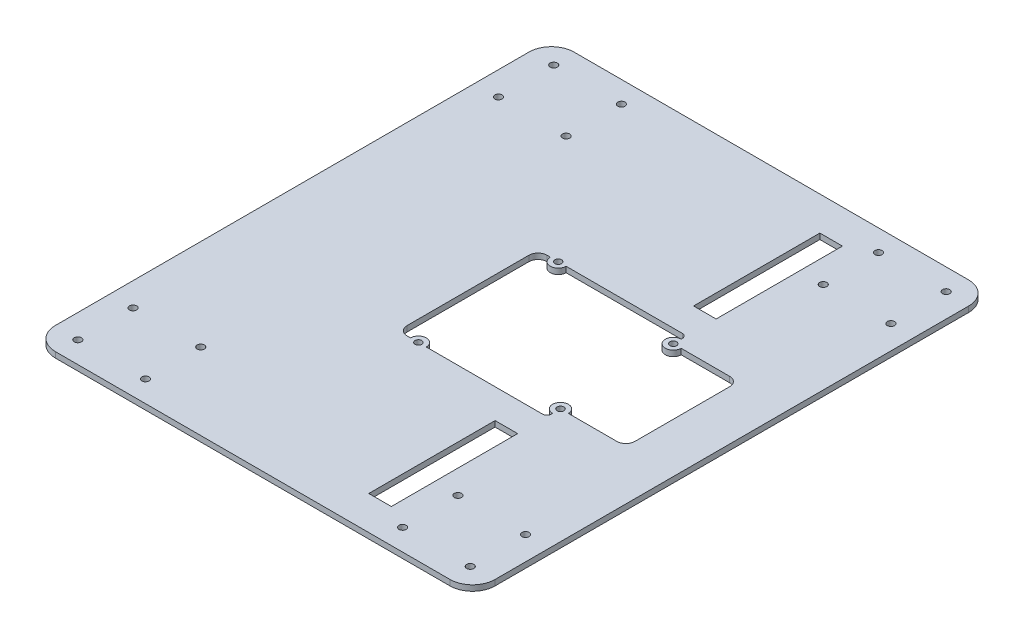
SolidWorks part; units mm, degrees
ref_plane "前视基准面" through (0, 0, 0) normal (0, 0, 1) x (1, 0, 0)
ref_plane "上视基准面" through (0, 0, 0) normal (0, 1, 0) x (1, 0, 0)
ref_plane "右视基准面" through (0, 0, 0) normal (1, 0, 0) x (0, 0, -1)
other "Configuration Table"
sketch "草图1" plane through (0, 0, 0) normal (0, 1, 0) x (1, 0, 0)
  line L0 (134, 15) -> (144, 15)
  line L1 (134, 215) -> (144, 215)
  line L5 (25.5, 220.5) -> (25.5, 196) construction
  line L9 (10.5, 220.5) -> (40.5, 220.5) construction
  line L10 (10.5, 220.5) -> (10.5, 196) construction
  line L43 (10.5, 196) -> (40.5, 196) construction
  line L44 (40.5, 220.5) -> (40.5, 196) construction
  line L45 (10.5, 208.25) -> (40.5, 208.25) construction
  line L46 (97.5, 230) -> (97.5, 0) construction
  line L47 (0, 0) -> (195, 0)
  line L48 (0, 0) -> (0, 230)
  line L49 (0, 230) -> (195, 230)
  line L50 (195, 0) -> (195, 230)
  line L51 (0, 230) -> (51, 230)
  line L52 (0, 230) -> (0, 186)
  line L53 (0, 186) -> (51, 186)
  line L54 (51, 230) -> (51, 186)
  line L55 (195, 230) -> (144, 230)
  line L56 (195, 230) -> (195, 186)
  line L57 (195, 186) -> (144, 186)
  line L58 (144, 230) -> (144, 186)
  line L59 (0, 0) -> (51, 0)
  line L60 (0, 0) -> (0, 44)
  line L61 (0, 44) -> (51, 44)
  line L62 (51, 0) -> (51, 44)
  line L63 (195, 0) -> (144, 0)
  line L64 (195, 0) -> (195, 44)
  line L65 (195, 44) -> (144, 44)
  line L66 (144, 0) -> (144, 44)
  line L67 (144, 230) -> (134, 230)
  line L68 (144, 230) -> (144, 159)
  line L69 (144, 159) -> (134, 159)
  line L70 (134, 230) -> (134, 159)
  line L71 (144, 0) -> (134, 0)
  line L72 (144, 0) -> (144, 71)
  line L73 (144, 71) -> (134, 71)
  line L74 (134, 0) -> (134, 71)
  line L75 (195, 115) -> (0, 115) construction
  circle A0 centre (10.5, 220.5) radius 1.6
  circle A1 centre (40.5, 220.5) radius 1.6
  circle A2 centre (40.5, 196) radius 1.6
  circle A3 centre (10.5, 196) radius 1.6
  circle A4 centre (184.5, 220.5) radius 1.6
  circle A5 centre (154.5, 220.5) radius 1.6
  circle A6 centre (154.5, 196) radius 1.6
  circle A7 centre (184.5, 196) radius 1.6
  circle A8 centre (154.5, 34) radius 1.6
  circle A9 centre (184.5, 34) radius 1.6
  circle A10 centre (184.5, 9.5) radius 1.6
  circle A11 centre (154.5, 9.5) radius 1.6
  circle A12 centre (40.5, 9.5) radius 1.6
  circle A13 centre (40.5, 34) radius 1.6
  circle A14 centre (10.5, 34) radius 1.6
  circle A15 centre (10.5, 9.5) radius 1.6
  point P4 (139, 15)
  point P5 (139, 71)
  dimension "D24" = 3.2
  dimension "D3" = 56
  dimension "D4" = 15
  dimension "D5" = 56
  dimension "D6" = 15
  dimension "D8" = 30
  dimension "D9" = 24.5
  dimension "D10" = 195
  dimension "D11" = 230
  dimension "D12" = 51
  dimension "D13" = 44
  dimension "D14" = 51
  dimension "D15" = 44
  dimension "D16" = 51
  dimension "D17" = 44
  dimension "D18" = 51
  dimension "D19" = 44
  dimension "D20" = 10
  dimension "D21" = 10
  dimension "D25" = 9.5
  dimension "D26" = 25.5
extrude "凸台-拉伸1" add sketch "草图1" along normal blind 2.5 contours L47 L74 L73 L72 L65 L50 L57 L68 L69 L70 L49 L54 L53 L48 L61 L62 | L54 L49 L48 L53 A3 A2 A1 A0 | L49 L58 L57 L50 A6 A4 A5 A7 | L47 L62 L61 L48 A14 A12 A13 A15 | L66 L47 L50 L65 A11 A10 A9 A8 | L74 L47 L66 L0 | L49 L70 L1 L58
sketch "草图2" plane through (0, 2.5, 0) normal (0, 1, 0) x (1, 0, 0)
  line L0 (0, 115) -> (195, 115) construction
  line L1 (87, 84) -> (87, 146) construction
  line L2 (144, 90) -> (144, 140) construction
  line L4 (78, 84) -> (144, 84)
  line L5 (78, 84) -> (78, 146)
  line L6 (78, 146) -> (144, 146)
  line L7 (144, 84) -> (144, 146)
  line L8 (144, 90) -> (173, 90)
  line L9 (144, 90) -> (144, 140)
  line L10 (144, 140) -> (173, 140)
  line L11 (173, 90) -> (173, 140)
  line L12 (0, 0) -> (195, 0)
  line L17 (195, 0) -> (195, 230)
  line L18 (195, 230) -> (0, 230)
  line L23 (0, 230) -> (0, 0)
  line L24 (0, 0) -> (195, 0)
  line L29 (195, 0) -> (195, 230)
  line L30 (195, 230) -> (0, 230)
  line L35 (0, 230) -> (0, 0)
  circle A0 centre (144, 90) radius 1.5
  circle A2 centre (87, 146) radius 1.5
  circle A3 centre (87, 84) radius 1.5
  circle A4 centre (144, 140) radius 1.5
  circle A5 centre (144, 90) radius 3.5
  circle A6 centre (144, 140) radius 3.5
  circle A7 centre (87, 84) radius 3.5
  circle A8 centre (87, 146) radius 3.5
  dimension "D4" = 3
  dimension "D5" = 3
  dimension "D10" = 7
  dimension "D11" = 7
  dimension "D12" = 7
  dimension "D13" = 7
  dimension "D2" = 50
  dimension "D3" = 62
  dimension "D6" = 57
  dimension "D8" = 95
  dimension "D9" = 66
  dimension "D1" = 0
extrude "切除-拉伸1" cut sketch "草图2" against normal up to surface (2.5 mm away) contours A3 L4 L7 L6 A2 L5 | A4 L10 L7 L8 A0 L11 | L8 A0 | L8 A0 | L10 A4 | L10 A4 | L6 A2 | L6 A2 | L4 A3 | L4 A3 | L7 A0 | L7 A4
fillet "圆角1" radius 10 4 edges at (0, 1.25, 0) (0, 1.25, -230) (195, 1.25, -230) (195, 1.25, 0)
fillet "圆角2" radius 4 4 edges at (78, 1.25, -146) (78, 1.25, -84) (173, 1.25, -140) (173, 1.25, -90)
fillet "圆角3" radius 2 2 edges at (144, 1.25, -146) (144, 1.25, -84)
